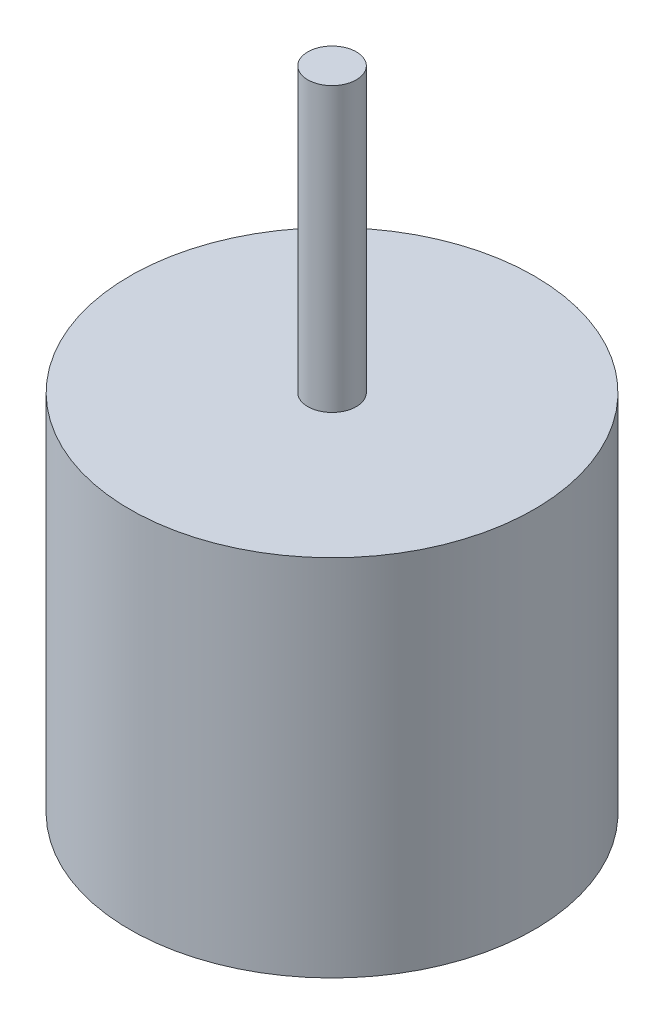
SolidWorks part; units mm, degrees
material "Plain Carbon Steel"
ref_plane "Front Plane" through (0, 0, 0) normal (0, 0, 1) x (1, 0, 0)
ref_plane "Top Plane" through (0, 0, 0) normal (0, 1, 0) x (1, 0, 0)
ref_plane "Right Plane" through (0, 0, 0) normal (1, 0, 0) x (0, 0, -1)
sketch "Sketch1" plane through (0, 0, 0) normal (0, 1, 0) x (1, 0, 0)
  circle A0 centre (0, 0) radius 25
  dimension "D1" = 50
extrude "Boss-Extrude1" add sketch "Sketch1" along normal blind 45
sketch "Sketch2" plane through (0, 45, 0) normal (0, 1, 0) x (1, 0, 0)
  circle A0 centre (0, 0) radius 3
  dimension "D1" = 6
extrude "Boss-Extrude2" add sketch "Sketch2" along normal blind 35
